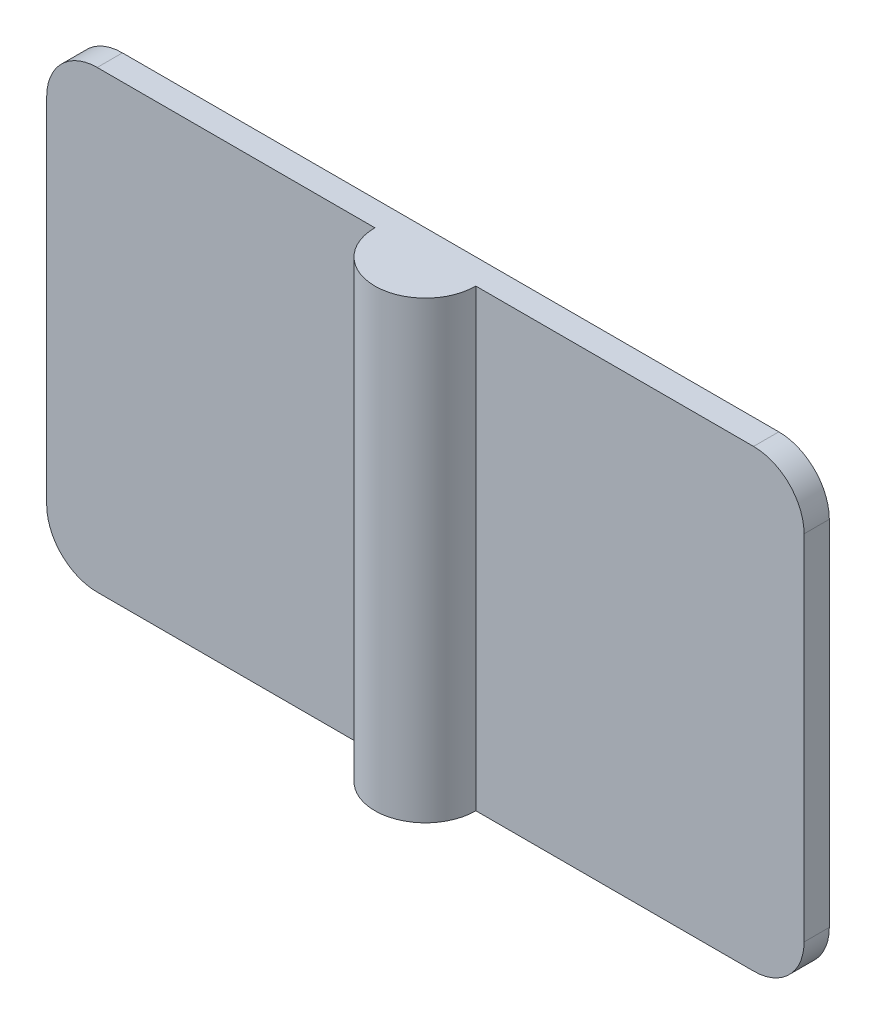
SolidWorks part; units mm, degrees
ref_plane "Front Plane" through (0, 0, 0) normal (0, 0, 1) x (1, 0, 0)
ref_plane "Top Plane" through (0, 0, 0) normal (0, 1, 0) x (1, 0, 0)
ref_plane "Right Plane" through (0, 0, 0) normal (1, 0, 0) x (0, 0, -1)
sketch "Sketch1" plane through (0, 0, 0) normal (0, 0, 1) x (1, 0, 0)
  line L0 (-457.6158, -52) -> (-421.8447, -52) construction
  line L1 (-454.7302, -43) -> (-424.7302, -43)
  line L2 (-454.7302, -43) -> (-454.7302, -61)
  line L3 (-454.7302, -61) -> (-424.7302, -61)
  line L4 (-424.7302, -43) -> (-424.7302, -61)
  line L5 (-457.6158, -59) -> (-457.6158, -45) construction
  line L6 (-439.7302, -52) -> (-439.7302, -32.2426) construction
  dimension "D1" = 18
  dimension "D2" = 9
  dimension "D3" = 30
  dimension "D4" = 15
extrude "Boss-Extrude1" add sketch "Sketch1" along normal blind 1
sketch "Sketch2" plane through (0, -43, 0) normal (0, 1, 0) x (1, 0, 0)
  line L0 (-424.7302, -1) -> (-454.7302, -1) construction
  line L2 (-437.7302, -1) -> (-441.7302, -1)
  line L3 (-454.7302, -1) -> (-454.7302, 0) construction
  arc A0 (-441.7302, -1) -> (-437.7302, -1) centre (-439.7302, -1) ccw
  dimension "D1" = 4
  dimension "D2" = 15
extrude "Boss-Extrude2" add sketch "Sketch2" against normal blind 18
fillet "Fillet1" radius 2
